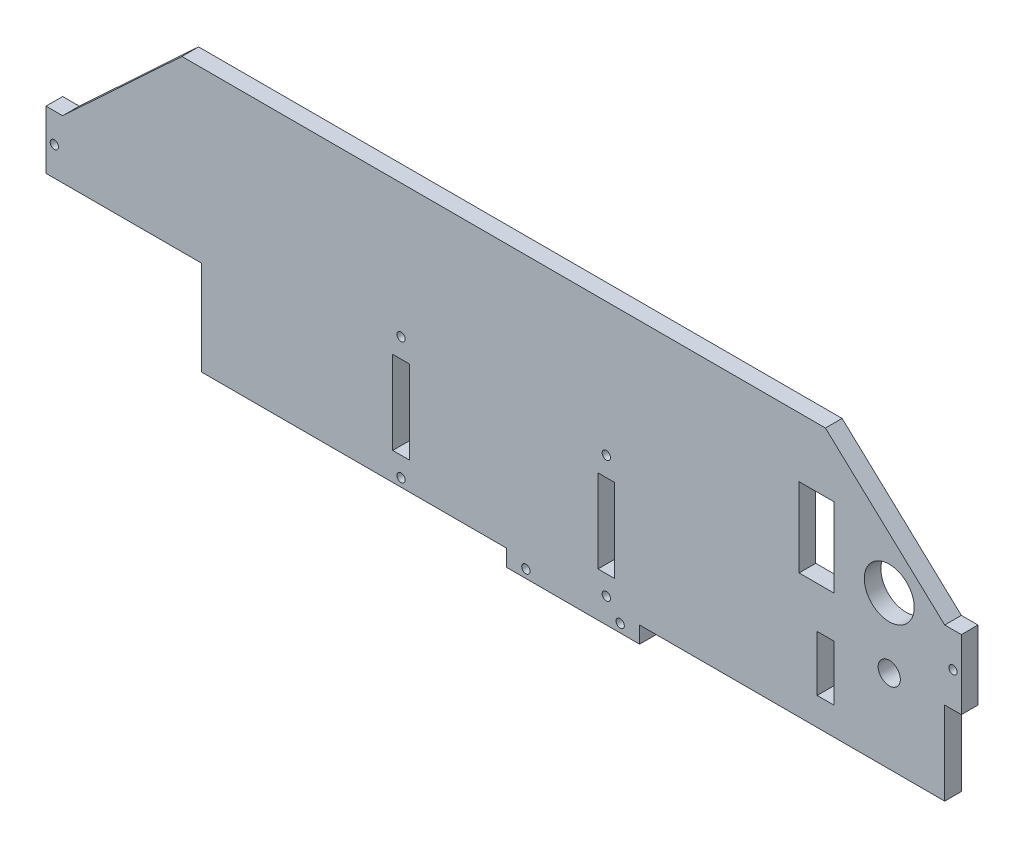
SolidWorks part; units mm, degrees
ref_plane "Plan de face" through (0, 0, 0) normal (0, 0, 1) x (1, 0, 0)
ref_plane "Plan de dessus" through (0, 0, 0) normal (0, 1, 0) x (1, 0, 0)
ref_plane "Plan de droite" through (0, 0, 0) normal (1, 0, 0) x (0, 0, -1)
sketch "Esquisse1" plane through (0, 0, 0) normal (0, 0, 1) x (1, 0, 0)
  line L0 (0, 0) -> (48, 0)
  line L1 (48, 0) -> (48, 6)
  line L2 (48, 6) -> (158, 6)
  line L3 (158, 6) -> (158, 36)
  line L4 (158, 36) -> (164, 36)
  line L5 (164, 36) -> (164, 61)
  line L6 (164, 61) -> (158, 61)
  line L7 (0, 0) -> (0, 6)
  line L8 (0, 6) -> (-110, 6)
  line L9 (-110, 6) -> (-110, 40)
  line L10 (-110, 40) -> (-166, 40)
  line L11 (-166, 40) -> (-166, 61)
  line L12 (-166, 61) -> (-160, 61)
  line L13 (-160, 61) -> (-117, 101.0027)
  line L14 (-117, 101.0027) -> (115, 101.0027)
  line L15 (115, 101.0027) -> (158, 61)
  dimension "D1" = 48
  dimension "D2" = 6
  dimension "D3" = 110
  dimension "D4" = 30
  dimension "D5" = 6
  dimension "D6" = 25
  dimension "D7" = 6
  dimension "D8" = 110
  dimension "D9" = 6
  dimension "D10" = 34
  dimension "D11" = 56
  dimension "D12" = 21
  dimension "D13" = 6
  dimension "D14" = 58.73
  dimension "D15" = 232
  dimension "D16" = 58.73
extrude "Boss.-Extru.1" add sketch "Esquisse1" along normal blind 6
sketch "Esquisse2" plane through (0, 0, 0) normal (0, 0, -1) x (-1, 0, 0)
  line L1 (41, 16) -> (35, 16)
  line L2 (41, 16) -> (41, 46)
  line L3 (41, 46) -> (35, 46)
  line L4 (35, 16) -> (35, 46)
  line L5 (-33, 16) -> (-39, 16)
  line L6 (-33, 16) -> (-33, 46)
  line L7 (-33, 46) -> (-39, 46)
  line L8 (-39, 16) -> (-39, 46)
  line L9 (110, 6) -> (0, 6) construction
  line L10 (110, 40) -> (110, 6) construction
  line L11 (-48, 6) -> (-158, 6) construction
  line L12 (-112, 16) -> (-118, 16)
  line L13 (-112, 16) -> (-112, 36)
  line L14 (-112, 36) -> (-118, 36)
  line L15 (-118, 16) -> (-118, 36)
  line L16 (-105.5, 51) -> (-118, 51)
  line L17 (-105.5, 51) -> (-105.5, 79.5)
  line L18 (-105.5, 79.5) -> (-118, 79.5)
  line L19 (-118, 51) -> (-118, 79.5)
  line L20 (-158, 6) -> (-158, 36) construction
  line L21 (-164, 36) -> (-164, 61) construction
  circle A0 centre (-138, 36) radius 4
  circle A1 centre (-138, 61) radius 9
  dimension "D11" = 8
  dimension "D14" = 18
  dimension "D15" = 30
  dimension "D18" = 25
  dimension "D1" = 30
  dimension "D2" = 6
  dimension "D3" = 30
  dimension "D4" = 6
  dimension "D5" = 80
  dimension "D6" = 10
  dimension "D7" = 10
  dimension "D8" = 69
  dimension "D9" = 6
  dimension "D10" = 20
  dimension "D12" = 28.5
  dimension "D13" = 12.5
  dimension "D16" = 20
  dimension "D17" = 26
  dimension "D19" = 10
  dimension "D20" = 15
  dimension "D21" = 20
  dimension "D22" = 20
extrude "Enlèv. mat.-Extru.1" cut sketch "Esquisse2" against normal blind 6
sketch "Esquisse3" plane through (0, 0, 0) normal (0, 0, -1) x (-1, 0, 0)
  line L0 (166, 61) -> (166, 40) construction
  line L1 (160, 61) -> (166, 61) construction
  line L2 (41, 16) -> (41, 46) construction
  line L3 (41, 46) -> (35, 46) construction
  line L4 (35, 16) -> (41, 16) construction
  line L5 (-39, 16) -> (-33, 16) construction
  line L6 (-33, 16) -> (-33, 46) construction
  line L7 (-48, 0) -> (-48, 6) construction
  line L8 (0, 0) -> (-48, 0) construction
  line L9 (0, 6) -> (0, 0) construction
  line L10 (-33, 46) -> (-39, 46) construction
  line L12 (-164, 36) -> (-164, 61) construction
  line L13 (-158, 36) -> (-164, 36) construction
  circle A0 centre (-161, 48.5) radius 1.5
  circle A1 centre (-41, 3) radius 1.5
  circle A2 centre (-7, 3) radius 1.5
  circle A3 centre (-36, 9) radius 1.5
  circle A4 centre (-36, 53) radius 1.5
  circle A5 centre (38, 9) radius 1.5
  circle A6 centre (38, 53) radius 1.5
  circle A7 centre (163, 50.5) radius 1.5
  point P41 (-161, 36)
  dimension "D1" = 3
  dimension "D3" = 10.5
  dimension "D4" = 3
  dimension "D5" = 3
  dimension "D6" = 7
  dimension "D7" = 3
  dimension "D8" = 3
  dimension "D9" = 7
  dimension "D10" = 3
  dimension "D11" = 7
  dimension "D12" = 3
  dimension "D13" = 3
  dimension "D14" = 7
  dimension "D15" = 3
  dimension "D16" = 3
  dimension "D17" = 7
  dimension "D18" = 3
  dimension "D19" = 3
  dimension "D20" = 7
  dimension "D21" = 3
  dimension "D22" = 3
  dimension "D23" = 3
  dimension "D24" = 12.5
  dimension "D2" = 3
extrude "Enlèv. mat.-Extru.2" cut sketch "Esquisse3" against normal blind 6
sketch "Esquisse4" plane through (0, 0, 0) normal (0, 0, -1) x (-1, 0, 0)
  circle A0 centre (38, 9) radius 2.995
  circle A1 centre (38, 53) radius 3
  circle A2 centre (-36, 53) radius 3
  circle A3 centre (-36, 9) radius 3
  circle A4 centre (-7, 3) radius 2.995
  circle A5 centre (-41, 3) radius 2.995
  circle A6 centre (-161, 48.5) radius 2.995
  circle A7 centre (163, 50.5) radius 2.995
  dimension "D1" = 5.99
  dimension "D2" = 6
  dimension "D3" = 5.99
  dimension "D4" = 6
  dimension "D5" = 5.99
  dimension "D6" = 5.99
  dimension "D7" = 6
  dimension "D8" = 5.99
extrude "Enlèv. mat.-Extru.3" cut sketch "Esquisse4" against normal blind 3
